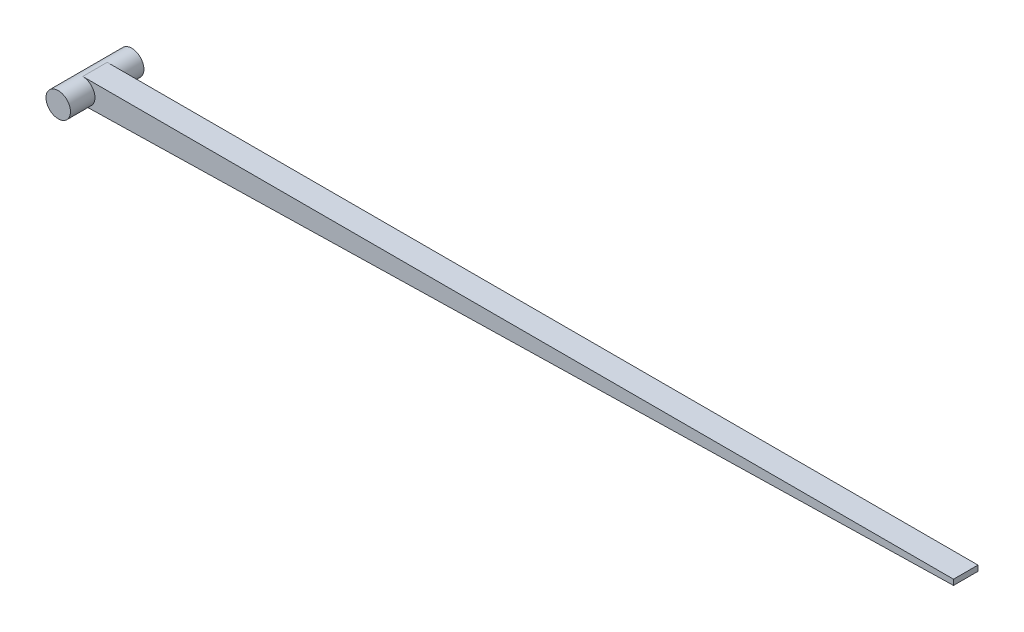
SolidWorks part; units mm, degrees
ref_plane "Front Plane" through (0, 0, 0) normal (0, 0, 1) x (1, 0, 0)
ref_plane "Top Plane" through (0, 0, 0) normal (0, 1, 0) x (1, 0, 0)
ref_plane "Right Plane" through (0, 0, 0) normal (1, 0, 0) x (0, 0, -1)
sketch "Sketch1" plane through (0, 0, 0) normal (0, 0, 1) x (1, 0, 0)
  line L0 (0, 0) -> (1600, 0)
  line L1 (1600, 0) -> (1600, -10)
  line L2 (1600, -10) -> (0, -45)
  line L3 (0, -45) -> (0, 0)
  dimension "D1" = 1600
  dimension "D2" = 45
  dimension "D3" = 10
extrude "Boss-Extrude1" add sketch "Sketch1" along normal blind 45
sketch "Sketch2" plane through (0, 0, 45) normal (0, 0, 1) x (1, 0, 0)
  line L0 (0, 0) -> (0, -45) construction
  circle A0 centre (0, -22.5) radius 22.5
extrude "Boss-Extrude2" add sketch "Sketch2" along normal blind 45 and the other way blind 90
